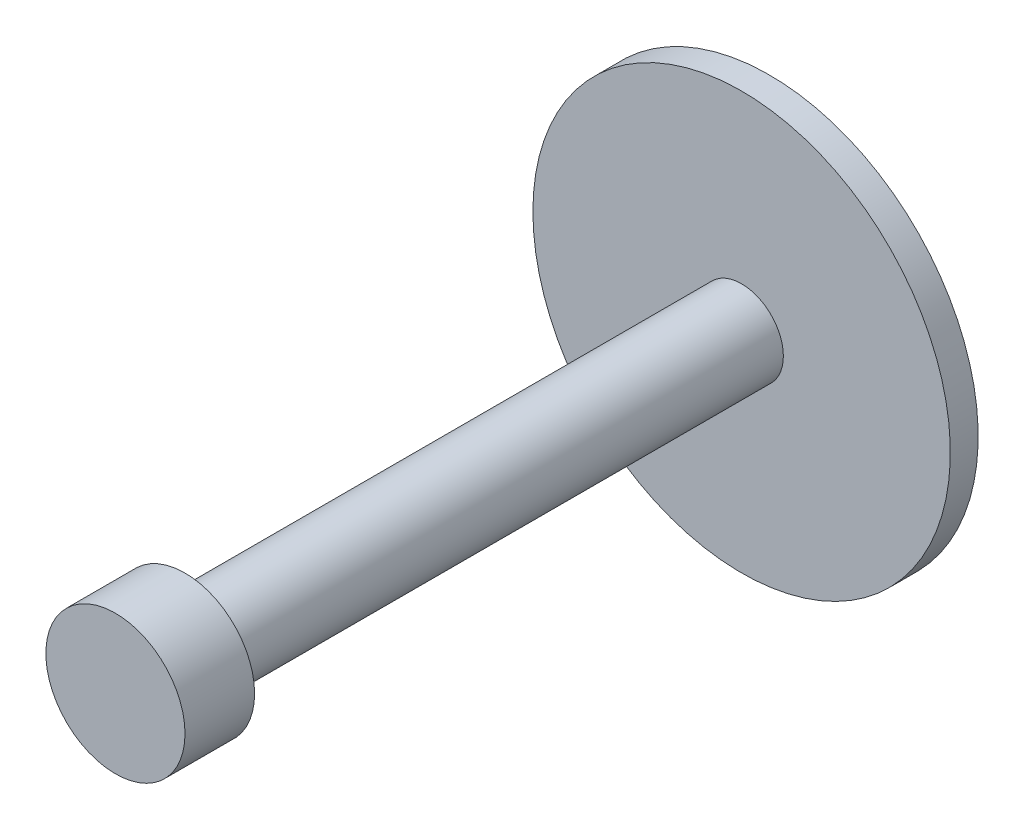
SolidWorks part; units mm, degrees
ref_plane "Front Plane" through (0, 0, 0) normal (0, 0, 1) x (1, 0, 0)
ref_plane "Top Plane" through (0, 0, 0) normal (0, 1, 0) x (1, 0, 0)
ref_plane "Right Plane" through (0, 0, 0) normal (1, 0, 0) x (0, 0, -1)
sketch "Sketch1" plane through (0, 0, 0) normal (0, 0, 1) x (1, 0, 0)
  circle A0 centre (0, 0) radius 15
  dimension "D1" = 30
extrude "Boss-Extrude1" add sketch "Sketch1" along normal blind 200
sketch "Sketch2" plane through (0, 0, 200) normal (0, 0, 1) x (1, 0, 0)
  circle A0 centre (0, 0) radius 25
  dimension "D1" = 50
extrude "Boss-Extrude2" add sketch "Sketch2" along normal blind 25
sketch "Sketch3" plane through (0, 0, 0) normal (0, 0, -1) x (-1, 0, 0)
  circle A0 centre (0, 0) radius 75
  dimension "D1" = 150
extrude "Boss-Extrude3" add sketch "Sketch3" along normal blind 10
sketch "Sketch4" plane through (0, 0, -10) normal (0, 0, -1) x (-1, 0, 0)
  circle A0 centre (0, 30) radius 7.5
  circle A1 centre (0, -30) radius 7.5
  dimension "D1" = 15
  dimension "D2" = 15
  dimension "D4" = 30
  dimension "D3" = 30
extrude "Cut-Extrude1" cut sketch "Sketch4" against normal blind 1
